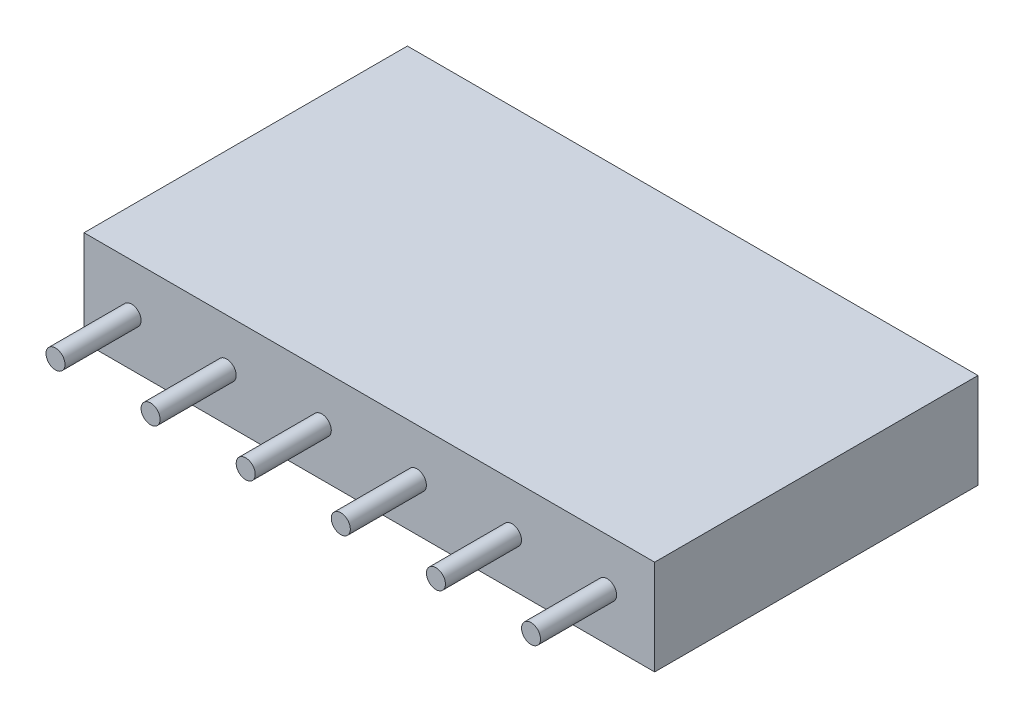
SolidWorks part; units mm, degrees
ref_plane "Plan de face" through (0, 0, 0) normal (0, 0, 1) x (1, 0, 0)
ref_plane "Plan de dessus" through (0, 0, 0) normal (0, 1, 0) x (1, 0, 0)
ref_plane "Plan de droite" through (0, 0, 0) normal (1, 0, 0) x (0, 0, -1)
sketch "Esquisse1" plane through (0, 0, 0) normal (0, 0, 1) x (1, 0, 0)
  line L1 (0, 0) -> (-2.5, 0)
  line L2 (0, 0) -> (0, 2.5)
  line L3 (0, 2.5) -> (-2.5, 2.5)
  line L4 (-2.5, 0) -> (-2.5, 2.5)
  dimension "D1" = 2.5
  dimension "D2" = 2.5
extrude "Boss.-Extru.1" add sketch "Esquisse1" along normal blind 8.5
sketch "Esquisse2" plane through (0, 0, 8.5) normal (0, 0, 1) x (1, 0, 0)
  line L0 (-2.5, 2.5) -> (0, 0) construction
  circle A0 centre (-1.25, 1.25) radius 0.25
  dimension "D1" = 0.5
extrude "Boss.-Extru.2" add sketch "Esquisse2" along normal blind 2
sketch "Esquisse3" plane through (0, 0, 0) normal (0, 0, -1) x (-1, 0, 0)
  line L0 (0, 2.5) -> (2.5, 0) construction
  circle A0 centre (1.25, 1.25) radius 0.25
  dimension "D1" = 0.5
extrude "Enlèv. mat.-Extru.2" cut sketch "Esquisse3" against normal blind 4
pattern_linear "Répétition linéaire1" count 6 spacing 2.5 along (-1, 0, 0) of "Boss.-Extru.1", "Enlèv. mat.-Extru.2", "Boss.-Extru.2"
